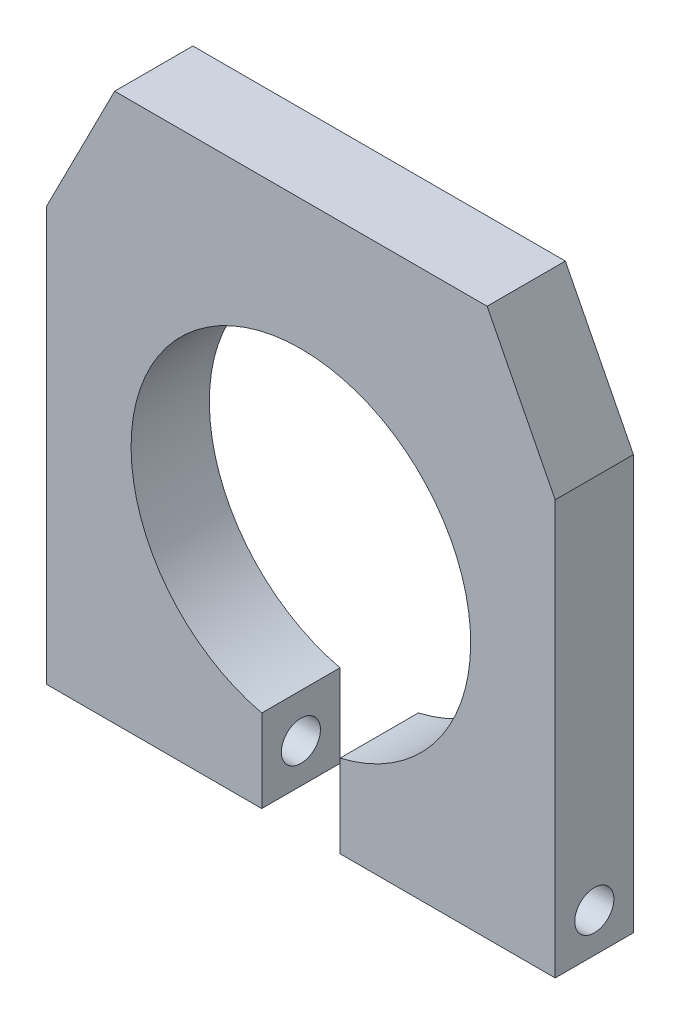
SolidWorks part; units mm, degrees
material "Alliage 1060"
ref_plane "Plan de face" through (0, 0, 0) normal (0, 0, 1) x (1, 0, 0)
ref_plane "Plan de dessus" through (0, 0, 0) normal (0, 1, 0) x (1, 0, 0)
ref_plane "Plan de droite" through (0, 0, 0) normal (1, 0, 0) x (0, 0, -1)
sketch "Esquisse1" plane through (0, 0, 0) normal (0, 0, 1) x (1, 0, 0)
  line L0 (34.925, -88.9) -> (34.925, -75.4585)
  line L1 (0, 0) -> (82.55, 0)
  line L2 (0, 0) -> (0, -88.9)
  line L3 (0, -88.9) -> (34.925, -88.9)
  line L4 (82.55, 0) -> (82.55, -88.9)
  line L5 (47.625, -88.9) -> (82.55, -88.9)
  line L6 (47.625, -75.4585) -> (47.625, -88.9)
  line L7 (34.925, -88.9) -> (47.625, -88.9) construction
  arc A0 (47.625, -75.4585) -> (34.925, -75.4585) centre (41.275, -48.641) ccw
  point P6 (41.275, -88.9)
  point P7 (41.275, 0)
  dimension "D3" = 55.118
  dimension "D1" = 82.55
  dimension "D2" = 88.9
  dimension "D4" = 12.7
  dimension "D5" = 12.7
extrude "Boss.-Extru.1" add sketch "Esquisse1" along normal blind 12.7
sketch "Esquisse2" plane through (82.55, 0, 0) normal (1, 0, 0) x (0, 0, -1)
  line L0 (-6.35, -82.55) -> (-12.7, -88.9) construction
  line L1 (-6.35, -82.55) -> (0, -88.9) construction
  line L2 (-6.35, -82.55) -> (-12.7, -82.55) construction
  line L3 (-12.7, -88.9) -> (-12.7, 0) construction
  line L4 (-6.35, -82.55) -> (-6.35, -88.9) construction
  line L5 (-12.7, -88.9) -> (0, -88.9) construction
  circle A0 centre (-6.35, -82.55) radius 3.175
  dimension "D1" = 6.35
extrude "Enlèv. mat.-Extru.1" cut sketch "Esquisse2" against normal through all
sketch "Esquisse3" plane through (0, 0, 12.7) normal (0, 0, 1) x (1, 0, 0)
  line L0 (11.049, 0) -> (71.501, 0) construction
  line L1 (82.55, 0) -> (0, 0) construction
  line L2 (11.049, 0) -> (0, -21.6849)
  line L3 (0, 0) -> (0, -88.9) construction
  line L4 (0, -21.6849) -> (0, 0)
  line L5 (0, 0) -> (11.049, 0)
  line L6 (71.501, 0) -> (82.55, 0)
  line L7 (82.55, 0) -> (82.55, -21.6849)
  line L8 (82.55, -88.9) -> (82.55, 0) construction
  line L9 (82.55, -21.6849) -> (71.501, 0)
  point P4 (41.275, 0)
  point P6 (41.275, 0)
  dimension "D1" = 27
  dimension "D2" = 60.452
extrude "Enlèv. mat.-Extru.2" cut sketch "Esquisse3" against normal through all
